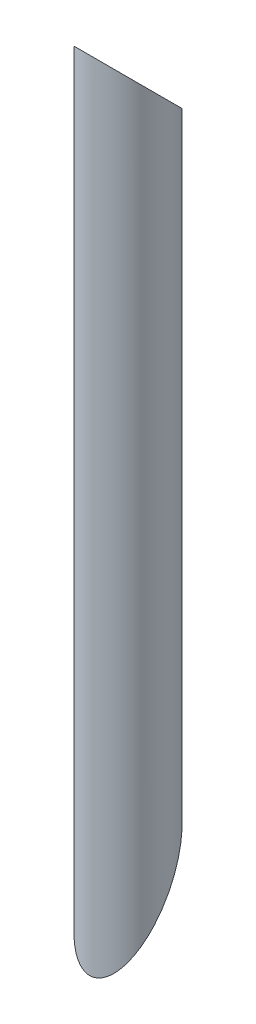
SolidWorks part; units mm, degrees
ref_plane "Front Plane" through (0, 0, 0) normal (0, 0, 1) x (1, 0, 0)
ref_plane "Top Plane" through (0, 0, 0) normal (0, 1, 0) x (1, 0, 0)
ref_plane "Right Plane" through (0, 0, 0) normal (1, 0, 0) x (0, 0, -1)
sketch "Sketch1" plane through (0, 0, 0) normal (0, 1, 0) x (1, 0, 0)
  circle A0 centre (0, 0) radius 6.35
  circle A1 centre (0, 0) radius 4.7625
  dimension "D1" = 12.7
  dimension "D2" = 9.525
extrude "Boss-Extrude1" add sketch "Sketch1" along normal blind 132.08
sketch "Sketch2" plane through (0, 0, 0) normal (1, 0, 0) x (0, 0, -1)
  line L0 (-6.35, 132.08) -> (6.35, 119.38)
  line L1 (6.35, 132.08) -> (-6.35, 132.08) construction
  line L2 (6.35, 0) -> (6.35, 132.08) construction
  line L3 (6.35, 119.38) -> (6.35, 132.08)
  line L4 (6.35, 132.08) -> (-6.35, 132.08)
  line L5 (-6.35, 132.08) -> (-6.35, 0) construction
  line L6 (-6.35, 0) -> (6.35, 21.997)
  line L7 (6.35, 0) -> (6.35, 132.08) construction
  line L8 (6.35, 21.997) -> (6.35, 0)
  line L9 (6.35, 0) -> (-6.35, 0)
  dimension "D1" = 45
  dimension "D2" = 30
extrude "Cut-Extrude1" cut sketch "Sketch2" against normal mid plane 132.08
ref_plane "Plane1" through (0, 0, -6.35) normal (0, 0, -1) x (-1, 0, 0)
